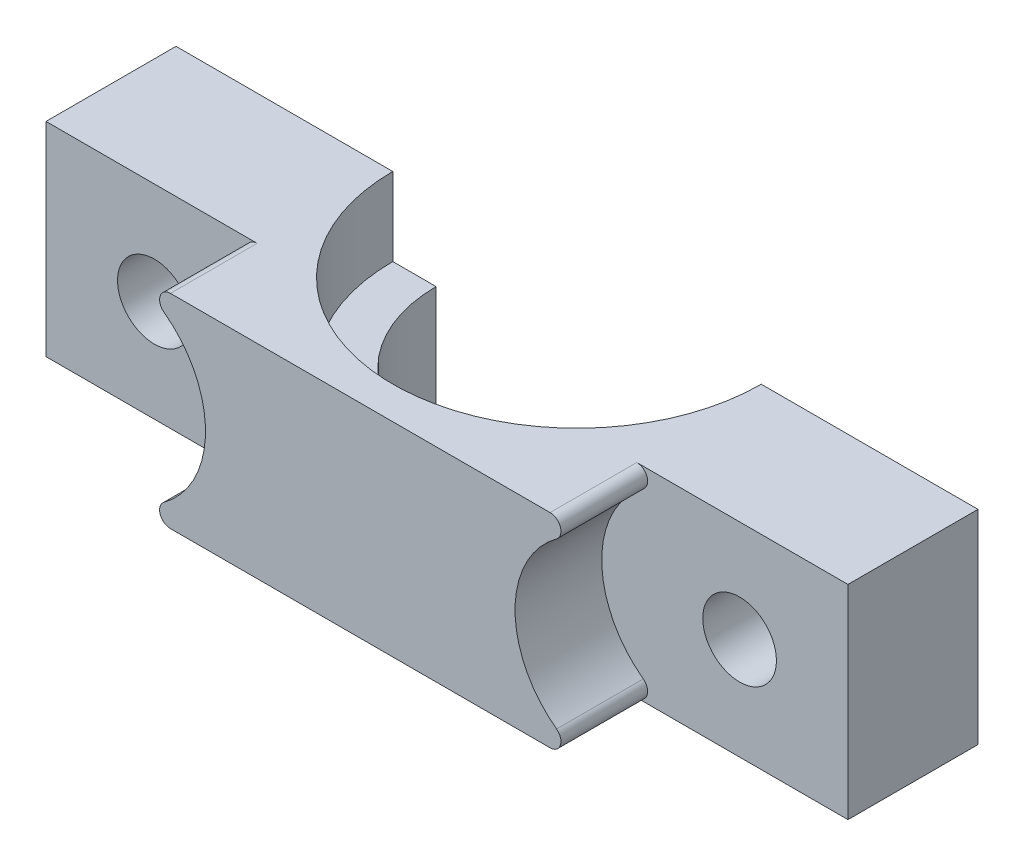
SolidWorks part; units mm, degrees
ref_plane "Front" through (0, 0, 0) normal (0, 0, 1) x (1, 0, 0)
ref_plane "Top" through (0, 0, 0) normal (0, 1, 0) x (1, 0, 0)
ref_plane "Right" through (0, 0, 0) normal (1, 0, 0) x (0, 0, -1)
sketch "Sketch1" plane through (0, 0, 0) normal (0, 1, 0) x (1, 0, 0)
  line L0 (-18.5, 0) -> (18.5, 0)
  line L1 (18.5, 0) -> (18.5, 10)
  line L2 (18.5, 10) -> (6.5, 10)
  line L3 (-6.5, 10) -> (-18.5, 10)
  line L4 (-18.5, 10) -> (-18.5, 0)
  line L5 (0, 18.1806) -> (0, -4.2196) construction
  arc A0 (6.5, 10) -> (-6.5, 10) centre (0, 10) cw
  dimension "D1" = 6.5
  dimension "D2" = 37
  dimension "D3" = 10
extrude "Boss-Extrude1" add sketch "Sketch1" along normal blind 5.8
sketch "Sketch7" plane through (0, 5.8, 0) normal (0, 1, 0) x (1, 0, 0)
  line L0 (-18.5, 10) -> (-18.5, 0)
  line L1 (-18.5, 0) -> (18.5, 0)
  line L2 (18.5, 0) -> (18.5, 10)
  line L3 (18.5, 10) -> (8.5, 10)
  line L4 (18.5, 10) -> (6.5, 10) construction
  line L5 (-18.5, 10) -> (-8.5, 10)
  line L6 (-6.5, 10) -> (-18.5, 10) construction
  arc A0 (-8.5, 10) -> (8.5, 10) centre (0, 10) ccw
  arc A1 (-6.5, 10) -> (6.5, 10) centre (0, 10) ccw construction
  dimension "D1" = 8.5
extrude "Boss-Extrude2" add sketch "Sketch7" along normal blind 3.6
hole_wizard "M3 Clearance Hole1" positions "Sketch3" profile "Sketch4" hole size "M3" standard "DIN" end condition through all
sketch "Sketch3" plane through (0, 0, 0) normal (0, 0, 1) x (1, 0, 0)
  line L0 (0, 10.9562) -> (0, -2.36) construction
  line L2 (-13.5, 11.76) -> (-13.5, -2.36) construction
  line L4 (-19.2001, 4.7) -> (46.2001, 4.7) construction
  line L5 (-18.5, 9.4) -> (18.5, 9.4) construction
  line L6 (-18.5, 0) -> (18.5, 0) construction
  point P0 (-13.5, 4.7)
  point P2 (13.5, 4.7)
sketch "Sketch4" plane through (-13.5, 4.7, 0) normal (1, 0, 0) x (0, -1, 0)
  line L0 (0, 0) -> (0, 10.0001)
  line L1 (0, 10.0001) -> (1.7, 10.0001)
  line L2 (1.7, 10.0001) -> (1.7, 0)
  line L5 (1.7, 0) -> (0, 0)
  line L11 (0, -6.35) -> (0, 107.95) construction
  dimension "Thru Hole Dia." = 3.4
  dimension "Thru Hole Depth" = 10.0001
sketch "Sketch5" plane through (0, 0, 0) normal (0, 0, 1) x (1, 0, 0)
  line L0 (-11.3955, 9.4) -> (-18.5, 9.4)
  line L2 (-18.5, 9.4) -> (-18.5, 0)
  line L3 (-18.5, 0) -> (-11.3955, 0)
  line L4 (20.9631, 4.7) -> (-21.5994, 4.7) construction
  line L5 (0, 8.4021) -> (0, -2.6012) construction
  line L6 (18.5, 0) -> (11.3955, 0)
  line L7 (18.5, 9.4) -> (18.5, 0)
  line L8 (11.3955, 9.4) -> (18.5, 9.4)
  line L11 (-18.5, 9.4) -> (-18.5, 0) construction
  line L12 (-18.5, 9.4) -> (18.5, 9.4) construction
  line L13 (-18.5, 0) -> (18.5, 0) construction
  arc A0 (-11.3955, 0) -> (-11.3955, 9.4) centre (-11.8634, 4.7) ccw
  arc A1 (11.3955, 0) -> (11.3955, 9.4) centre (11.8634, 4.7) cw
extrude "Cut-Extrude1" cut sketch "Sketch5" against normal blind 4
fillet "Fillet1" radius 0.5 4 edges at (11.3955, 0, -2) (-11.3955, 0, -2) (11.3955, 9.4, -2) (-11.3955, 9.4, -2)
